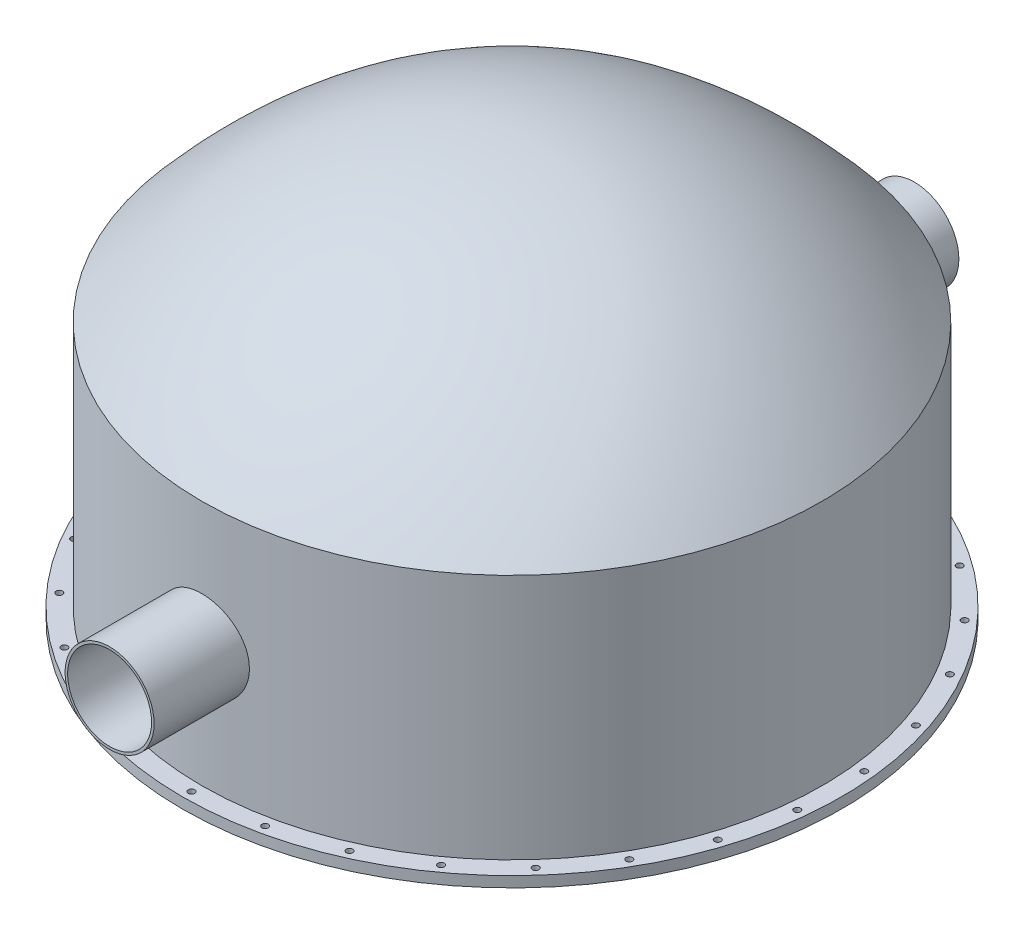
SolidWorks part; units mm, degrees
ref_plane "Front Plane" through (0, 0, 0) normal (0, 0, 1) x (1, 0, 0)
ref_plane "Top Plane" through (0, 0, 0) normal (0, 1, 0) x (1, 0, 0)
ref_plane "Right Plane" through (0, 0, 0) normal (1, 0, 0) x (0, 0, -1)
sketch "Sketch1" plane through (0, 0, 0) normal (1, 0, 0) x (0, 0, -1)
  line L0 (877.1128, 0) -> (0, 0) construction
  line L1 (0, 0) -> (0, 1044.41) construction
  line L2 (-2081.13, 0) -> (-2081.13, -1744.115)
  line L3 (-931.3985, 1044.41) -> (931.3985, 1044.41) construction
  line L4 (-2126.02, 16.9087) -> (-2126.02, -1671.115)
  line L5 (-2081.13, -1744.115) -> (-2258.02, -1744.115)
  line L6 (-2258.02, -1744.115) -> (-2258.02, -1671.115)
  line L7 (-2258.02, -1671.115) -> (-2126.02, -1671.115)
  line L8 (0, 1089.3) -> (0, 1044.41)
  line L9 (-2126.02, 16.9087) -> (-2126.02, -1744.115) construction
  spline S0 degree 2 poles (0, 1044.41) (-1164.2481, 1044.41) (-2081.13, 0) knots 0 0 0 1 1 1
  spline S1 degree 1 poles (0, 1089.3) (-2126.02, 16.9087) knots 0 0 1 1 construction
  spline S2 degree 3 poles (0, 1089.3) (-12.393, 1089.3) (-37.2065, 1089.125) (-86.6057, 1088.0745) (-148.0819, 1085.4478) (-221.3651, 1080.1928) (-294.1699, 1072.8341) (-366.4897, 1063.3711) (-462.2657, 1047.9476) (-580.7573, 1023.4067) (-720.9535, 985.5434) (-859.1292, 939.2749) (-995.26, 884.6147) (-1129.3253, 821.5798) (-1261.3088, 750.1894) (-1391.1991, 670.4639) (-1518.9895, 582.4237) (-1644.6775, 486.088) (-1747.6666, 398.9103) (-1829.0093, 325.037) (-1889.4928, 267.5681) (-1949.4537, 208.0371) (-1998.9863, 156.7105) (-2038.3521, 114.6194) (-2062.8472, 87.8837) (-2082.3787, 66.2374) (-2094.5579, 52.6025) (-2104.2873, 41.6273) (-2110.3563, 34.7477) (-2115.219, 29.2126) (-2120.0089, 23.7555) (-2123.6178, 19.6451) (-2126.02, 16.9087) knots 0 0 0 0 0.01572 0.03144 0.06288 0.09432 0.12576 0.157201 0.188641 0.251521 0.314401 0.377281 0.440161 0.503042 0.565922 0.628802 0.691682 0.754562 0.817443 0.848883 0.880323 0.911763 0.943203 0.958923 0.974643 0.982503 0.990363 0.994293 0.998223 1.000188 1.002153 1.006083 1.006083 1.006083 1.006083
  dimension "D1" = 1044.41
  dimension "D2" = 2081.13
  dimension "D3" = 1744.115
  dimension "D5" = 132
  dimension "D6" = 73
  dimension "D4" = 44.89
revolve "Revolve1" add sketch "Sketch1" angle 360 about L8
ref_plane "Plane1" through (0, 0, 2757) normal (0, 0, 1) x (1, 0, 0)
sketch "Sketch2" plane through (0, 0, 2757) normal (0, 0, 1) x (1, 0, 0)
  line L0 (-2258.02, -1744.115) -> (2258.02, -1744.115) construction
  circle A0 centre (0, -835.615) radius 304.8
  point P5 (0, 0)
  dimension "D1" = 609.6
  dimension "D2" = 908.5
extrude "Boss-Extrude1" add sketch "Sketch2" against normal up to surface up to face at (0, -1671.115, 2126.02)
mirror "Mirror1" about plane through (0, 0, 0) normal (0, 0, 1) of "Boss-Extrude1"
sketch "Sketch3" plane through (0, 0, 2757) normal (0, 0, 1) x (1, 0, 0)
  circle A0 centre (0, -835.615) radius 287.4
  dimension "D1" = 574.8
extrude "Cut-Extrude1" cut sketch "Sketch3" against normal through all
sketch "Sketch4" plane through (0, -1744.115, 0) normal (0, -1, 0) x (1, 0, 0)
  circle A0 centre (0, 0) radius 2196.0235 construction
  circle A1 centre (0, 2196.0235) radius 22
  circle A2 centre (456.579, 2148.0351) radius 22
  circle A3 centre (893.2032, 2006.1673) radius 22
  circle A4 centre (1290.7902, 1776.6203) radius 22
  circle A5 centre (1631.9635, 1469.4265) radius 22
  circle A6 centre (1901.8121, 1098.0118) radius 22
  circle A7 centre (2088.5425, 678.6086) radius 22
  circle A8 centre (2183.9935, 229.547) radius 22
  circle A9 centre (2183.9935, -229.547) radius 22
  circle A10 centre (2088.5425, -678.6086) radius 22
  circle A11 centre (1901.8121, -1098.0117) radius 22
  circle A12 centre (1631.9635, -1469.4265) radius 22
  circle A13 centre (1290.7902, -1776.6203) radius 22
  circle A14 centre (893.2032, -2006.1673) radius 22
  circle A15 centre (456.579, -2148.0351) radius 22
  circle A16 centre (0, -2196.0235) radius 22
  circle A17 centre (-456.579, -2148.0351) radius 22
  circle A18 centre (-893.2032, -2006.1673) radius 22
  circle A19 centre (-1290.7902, -1776.6203) radius 22
  circle A20 centre (-1631.9635, -1469.4265) radius 22
  circle A21 centre (-1901.8121, -1098.0118) radius 22
  circle A22 centre (-2088.5425, -678.6086) radius 22
  circle A23 centre (-2183.9935, -229.547) radius 22
  circle A24 centre (-2183.9935, 229.547) radius 22
  circle A25 centre (-2088.5425, 678.6086) radius 22
  circle A26 centre (-1901.8121, 1098.0117) radius 22
  circle A27 centre (-1631.9635, 1469.4265) radius 22
  circle A28 centre (-1290.7902, 1776.6203) radius 22
  circle A29 centre (-893.2032, 2006.1673) radius 22
  circle A30 centre (-456.579, 2148.0351) radius 22
  point P66 (0, 0)
  dimension "D1" = 44
  dimension "D2" = 30
extrude "Cut-Extrude2" cut sketch "Sketch4" against normal up to next (73 mm away)
